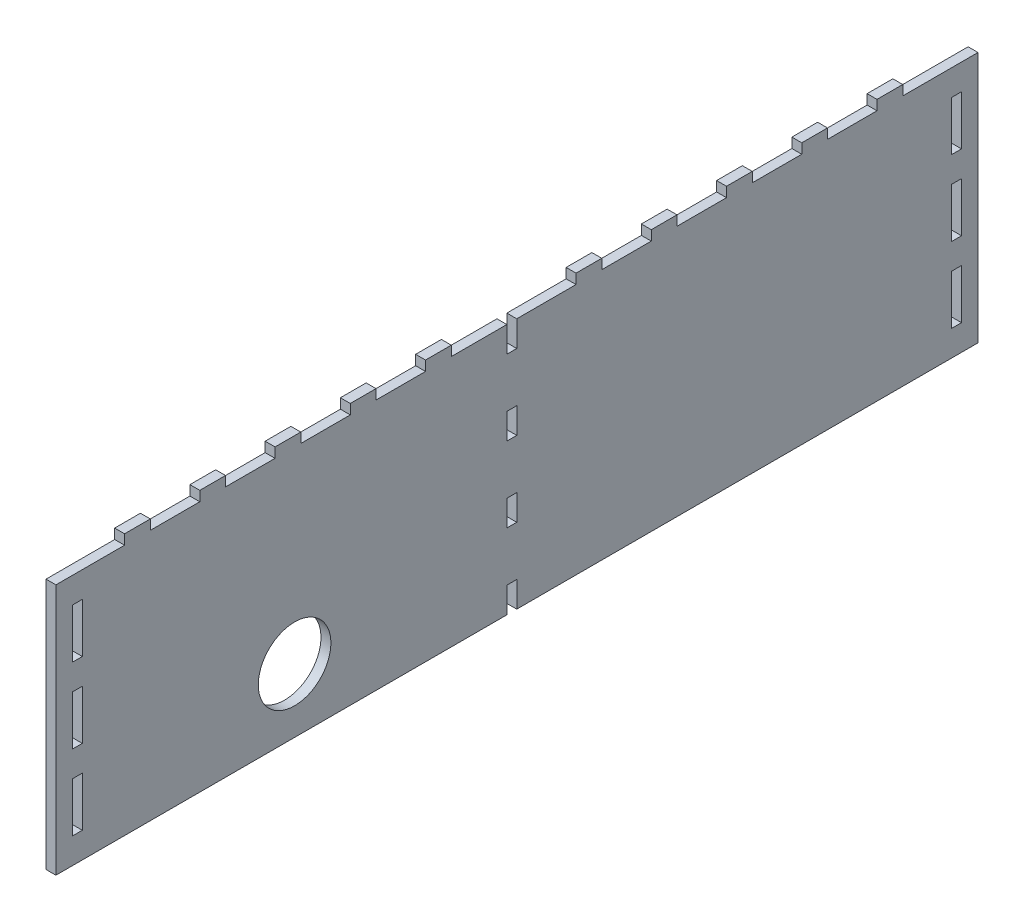
SolidWorks part; units mm, degrees
material "ENPH 253 Hardboard"
ref_plane "Front Plane" through (0, 0, 0) normal (0, 0, 1) x (1, 0, 0)
ref_plane "Top Plane" through (0, 0, 0) normal (0, 1, 0) x (1, 0, 0)
ref_plane "Right Plane" through (0, 0, 0) normal (1, 0, 0) x (0, 0, -1)
sketch "Sketch1" plane through (0, 0, 0) normal (1, 0, 0) x (0, 0, -1)
  line L1 (-139.7, 38.1) -> (139.7, 38.1)
  line L2 (-139.7, 38.1) -> (-139.7, -38.1)
  line L3 (-139.7, -38.1) -> (139.7, -38.1)
  line L4 (139.7, 38.1) -> (139.7, -38.1)
  line L5 (-139.7, 38.1) -> (139.7, -38.1) construction
  line L6 (-139.7, -38.1) -> (139.7, 38.1) construction
  point P0 (0, 0)
  dimension "D1" = 279.4
  dimension "D2" = 76.2
extrude "Boss-Extrude1" add sketch "Sketch1" against normal blind 3 contours L2 L3 L4 L1
sketch "Sketch3" plane through (-3, 0, 0) normal (-1, 0, 0) x (0, 0, 1)
  line L0 (-139.7, 38.1) -> (-139.7, -38.1) construction
  line L1 (139.7, 38.1) -> (139.7, -38.1) construction
  line L2 (139.7, 38.1) -> (-139.7, 38.1) construction
  line L3 (134.7, 30.3) -> (131.7, 30.3)
  line L4 (134.7, 30.3) -> (134.7, 15.3)
  line L5 (134.7, 15.3) -> (131.7, 15.3)
  line L6 (131.7, 30.3) -> (131.7, 15.3)
  line L7 (139.7, 38.1) -> (139.7, -38.1) construction
  circle A0 centre (69.85, 0) radius 50.8 construction
  circle A1 centre (-69.85, 0) radius 50.8 construction
  dimension "D1" = 101.6
  dimension "D2" = 101.6
  dimension "D3" = 69.85
  dimension "D4" = 69.85
  dimension "D5" = 15
  dimension "D6" = 7.8
  dimension "D7" = 5
  dimension "D8" = 3
extrude "Cut-Extrude1" cut sketch "Sketch3" against normal through all
pattern_linear "LPattern1" count 3 spacing 22.8 along (0, -1, 0) of "Cut-Extrude1"
mirror "Mirror1" about plane through (0, 0, 0) normal (0, 0, 1) of "LPattern1", "Cut-Extrude1"
sketch "Sketch6" plane through (-3, 0, 0) normal (-1, 0, 0) x (0, 0, 1)
  line L0 (139.7, 38.1) -> (-139.7, 38.1) construction
  line L1 (0.06, 38.1) -> (3.06, 38.1)
  line L2 (0.06, 38.1) -> (0.06, 30.3)
  line L3 (0.06, 30.3) -> (3.06, 30.3)
  line L4 (3.06, 38.1) -> (3.06, 30.3)
  dimension "D1" = 136.64
  dimension "D2" = 3
  dimension "D3" = 7.8
extrude "Cut-Extrude2" cut sketch "Sketch6" against normal through all
pattern_linear "LPattern2" count 4 spacing 22.8 along (0, -1, 0) of "Cut-Extrude2"
sketch "Sketch8" plane through (0, 38.1, 0) normal (0, 1, 0) x (1, 0, 0)
  line L0 (0, -139.7) -> (0, -3.06) construction
  line L1 (0, 116.9) -> (-3, 116.9)
  line L2 (0, 116.9) -> (0, 109.1)
  line L3 (0, 109.1) -> (-3, 109.1)
  line L4 (-3, 116.9) -> (-3, 109.1)
  line L5 (-3, -139.7) -> (-3, -3.06) construction
  line L7 (-3, 139.7) -> (0, 139.7) construction
  dimension "D1" = 22.8
  dimension "D2" = 7.8
extrude "Boss-Extrude2" add sketch "Sketch8" along normal blind 3
pattern_linear "LPattern4" count 11 spacing 22.8 along (0, 0, 1) skipping (5, 0) of "Boss-Extrude2"
sketch "Sketch9" plane through (-3, 0, 0) normal (-1, 0, 0) x (0, 0, 1)
  line L0 (139.7, -38.1) -> (3.06, -38.1) construction
  line L1 (3.06, -15.3) -> (3.06, -7.5) construction
  circle A0 centre (67.38, -18.8) radius 11
  point P2 (0, 0)
  dimension "D1" = 22
  dimension "D2" = 19.3
  dimension "D3" = 64.32
extrude "Cut-Extrude3" cut sketch "Sketch9" against normal through all contours A0
equation "\"D4@Sketch3\"=\"D3@Sketch3\""
